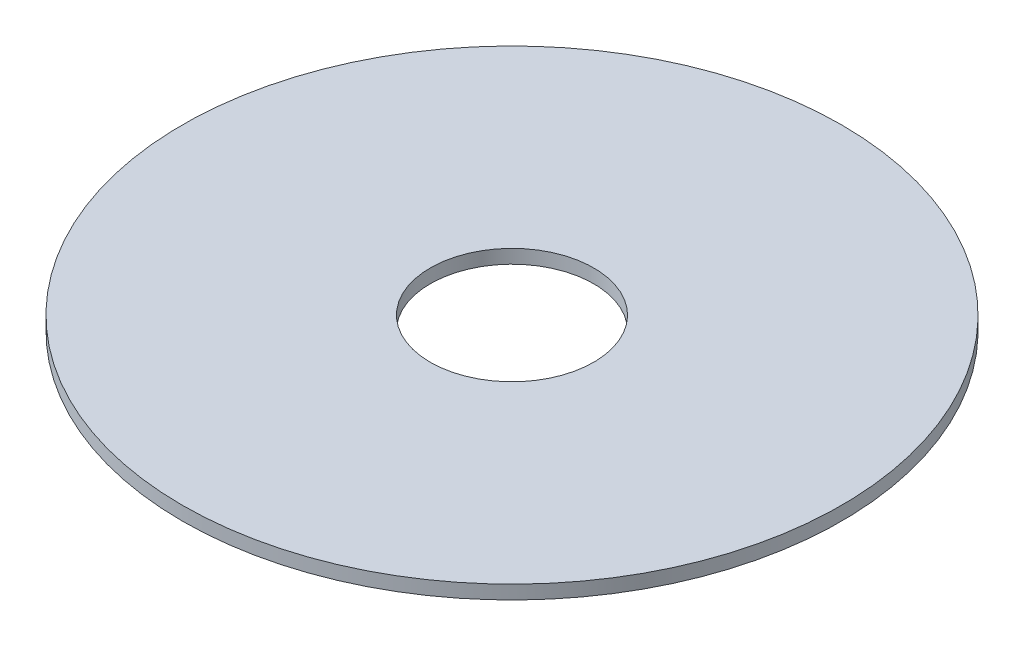
SolidWorks part; units mm, degrees
material "Custom Plastic"
ref_plane "Front Plane" through (0, 0, 0) normal (0, 0, 1) x (1, 0, 0)
ref_plane "Top Plane" through (0, 0, 0) normal (0, 1, 0) x (1, 0, 0)
ref_plane "Right Plane" through (0, 0, 0) normal (1, 0, 0) x (0, 0, -1)
sketch "Sketch1" plane through (0, 0, 0) normal (0, 1, 0) x (1, 0, 0)
  line L7 (-21.3316, 0) -> (0, 0) construction
  circle A0 centre (0, 0) radius 38.1
  circle A1 centre (0, 0) radius 9.4488
  point P0 (0, 0)
  dimension "D1" = 76.2
  dimension "D2" = 18.8976
extrude "Boss-Extrude1" add sketch "Sketch1" along normal blind 1.5875
